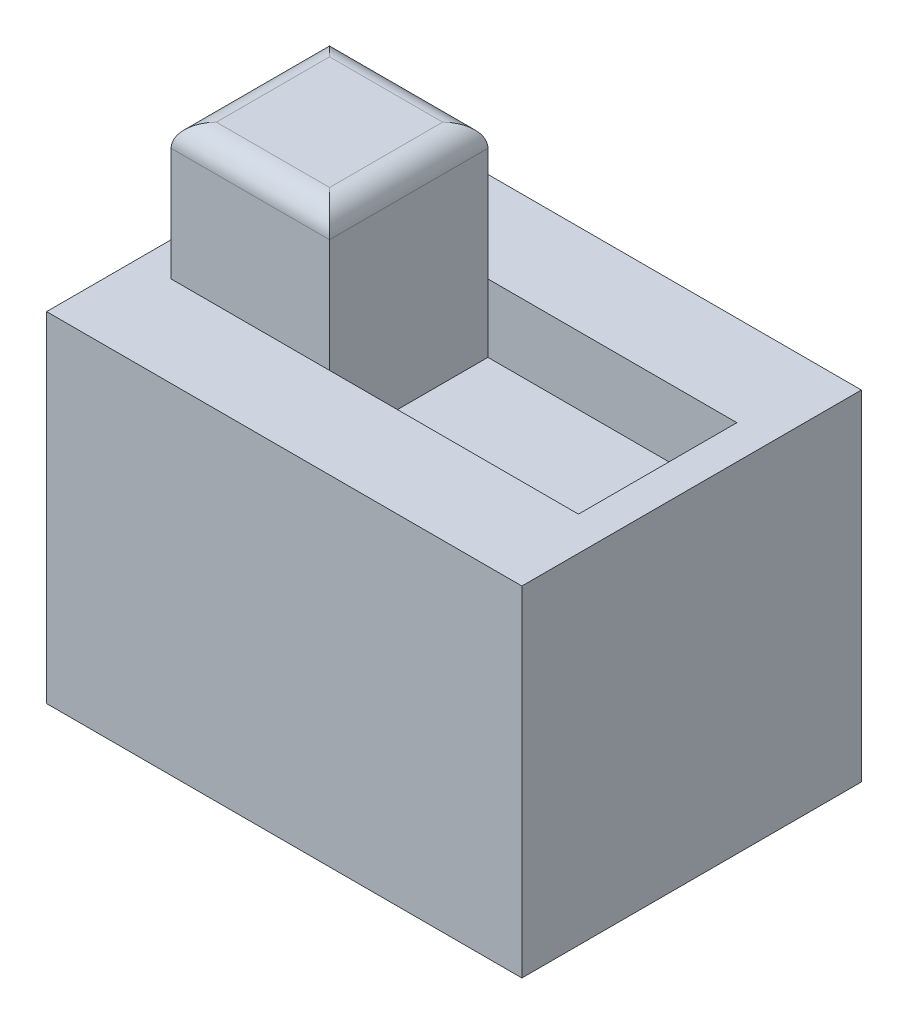
SolidWorks part; units mm, degrees
ref_plane "Front" through (0, 0, 0) normal (0, 0, 1) x (1, 0, 0)
ref_plane "Top" through (0, 0, 0) normal (0, 1, 0) x (1, 0, 0)
ref_plane "Right" through (0, 0, 0) normal (1, 0, 0) x (0, 0, -1)
sketch "Sketch1" plane through (0, 0, 0) normal (0, 1, 0) x (1, 0, 0)
  line L1 (-10.5, -7.5) -> (10.5, -7.5)
  line L2 (-10.5, -7.5) -> (-10.5, 7.5)
  line L3 (-10.5, 7.5) -> (10.5, 7.5)
  line L4 (10.5, -7.5) -> (10.5, 7.5)
  line L5 (-10.5, -7.5) -> (10.5, 7.5) construction
  line L6 (-10.5, 7.5) -> (10.5, -7.5) construction
  point P0 (0, 0)
  dimension "D1" = 21
  dimension "D2" = 15
extrude "Boss-Extrude1" add sketch "Sketch1" along normal blind 15
sketch "Sketch3" plane through (0, 15, 0) normal (0, 1, 0) x (1, 0, 0)
  line L1 (-9, -3.5) -> (9, -3.5)
  line L2 (-9, -3.5) -> (-9, 3.5)
  line L3 (-9, 3.5) -> (9, 3.5)
  line L4 (9, -3.5) -> (9, 3.5)
  line L5 (-9, -3.5) -> (9, 3.5) construction
  line L6 (-9, 3.5) -> (9, -3.5) construction
  point P0 (0, 0)
  dimension "D1" = 18
  dimension "D2" = 7
extrude "Cut-Extrude1" cut sketch "Sketch3" against normal blind 3
sketch "Sketch4" plane through (0, 12, 0) normal (0, 1, 0) x (1, 0, 0)
  line L0 (9, 3.5) -> (-9, 3.5) construction
  line L1 (-9, -3.5) -> (-2, -3.5)
  line L2 (-9, -3.5) -> (-9, 3.5)
  line L3 (-9, 3.5) -> (-2, 3.5)
  line L4 (-2, -3.5) -> (-2, 3.5)
  dimension "D1" = 7
extrude "Boss-Extrude3" add sketch "Sketch4" along normal blind 9
fillet "Fillet2" radius 1 4 edges at (-5.5, 21, -3.5) (-2, 21, 0) (-5.5, 21, 3.5) (-9, 21, 0)
